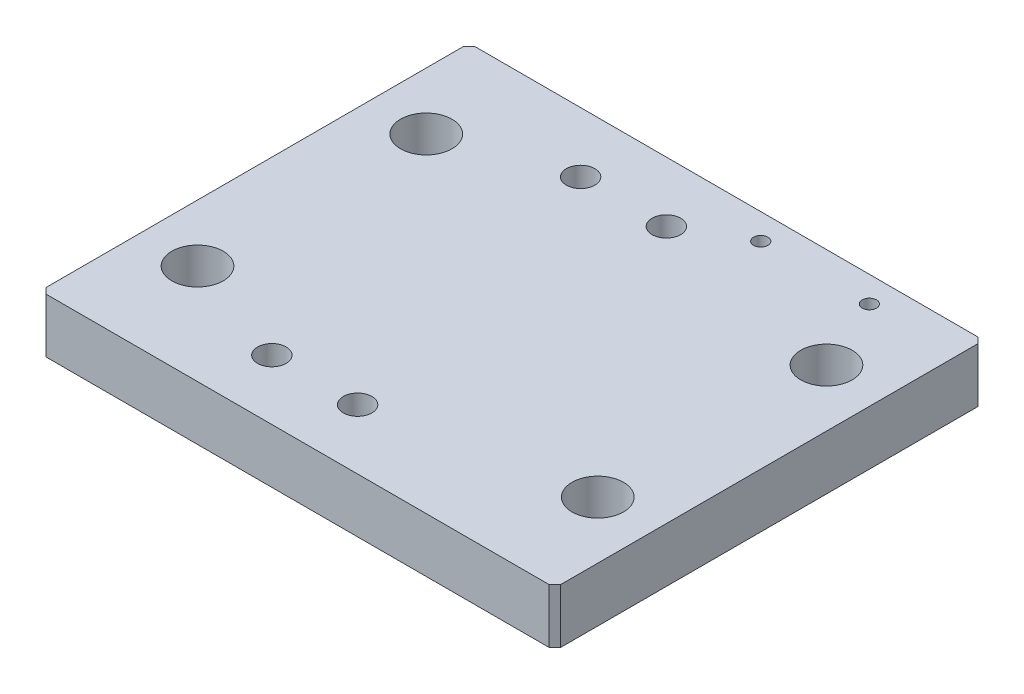
SolidWorks part; units mm, degrees
material "6063-T6"
ref_plane "Front Plane" through (0, 0, 0) normal (0, 0, 1) x (1, 0, 0)
ref_plane "Top Plane" through (0, 0, 0) normal (0, 1, 0) x (1, 0, 0)
ref_plane "Right Plane" through (0, 0, 0) normal (1, 0, 0) x (0, 0, -1)
sketch "Sketch1" plane through (0, 0, 0) normal (0, 1, 0) x (1, 0, 0)
  line L0 (10.5, 33) -> (29.5, 33) construction
  line L1 (-45, 37.5) -> (45, 37.5)
  line L2 (-45, 37.5) -> (-45, -37.5)
  line L3 (-45, -37.5) -> (45, -37.5)
  line L4 (45, 37.5) -> (45, -37.5)
  line L5 (-45, 37.5) -> (45, -37.5) construction
  line L6 (-45, -37.5) -> (45, 37.5) construction
  line L7 (35, 20) -> (-35, 20) construction
  line L8 (35, 20) -> (35, -20) construction
  line L9 (35, -20) -> (-35, -20) construction
  line L10 (-35, 20) -> (-35, -20) construction
  line L11 (35, 20) -> (-35, -20) construction
  line L12 (35, -20) -> (-35, 20) construction
  line L13 (-15, 27) -> (0, 27) construction
  line L14 (-15, 27) -> (-15, -27) construction
  line L15 (-15, -27) -> (0, -27) construction
  line L16 (0, 27) -> (0, -27) construction
  point P0 (0, 0)
  point P6 (0, 0)
  point P17 (20, 33)
  dimension "B" = 15
  dimension "A" = 54
  dimension "D3" = 70
  dimension "D4" = 40
  dimension "D6" = 10
  dimension "D7" = 19
  dimension "D8" = 20
  dimension "D9" = 33
  dimension "C" = 75
extrude "Boss-Extrude1" add sketch "Sketch1" along normal blind 9.525
hole_wizard "M8 Clearance Hole1" positions "Sketch2" profile "Sketch3" hole size "M8" standard "ANSI Metric" end condition through all
sketch "Sketch2" plane through (0, 9.525, 0) normal (0, 1, 0) x (1, 0, 0)
  point P0 (-35, 20)
  point P3 (35, 20)
  point P6 (35, -20)
  point P9 (-35, -20)
sketch "Sketch3" plane through (-35, 9.525, -20) normal (1, 0, 0) x (0, 0, 1)
  line L0 (0, 0) -> (0, 9.525)
  line L1 (0, 9.525) -> (4.5, 9.525)
  line L2 (4.5, 9.525) -> (4.5, 0)
  line L5 (4.5, 0) -> (0, 0)
  line L11 (0, -6.35) -> (0, 107.95) construction
  dimension "Thru Hole Dia." = 9
  dimension "Thru Hole Depth" = 9.525
hole_wizard "Fixed M6x1.0 Tapped Hole1" positions "Sketch4" profile "Sketch5" tap size "M6x1.0" standard "ANSI Metric" end condition up to next
sketch "Sketch4" plane through (0, 9.525, 0) normal (0, 1, 0) x (1, 0, 0)
  point P0 (-15, 27)
  point P3 (0, 27)
  point P6 (0, -27)
  point P9 (-15, -27)
sketch "Sketch5" plane through (-15, 9.525, -27) normal (1, 0, 0) x (0, 0, 1)
  line L0 (0, 0) -> (0, 9.525)
  line L1 (0, 9.525) -> (2.5, 9.525)
  line L2 (2.5, 9.525) -> (2.5, 0)
  line L5 (2.5, 0) -> (0, 0)
  line L11 (0, -6.35) -> (0, 107.95) construction
  dimension "Thru Tap Drill Dia." = 5
  dimension "Thru Tap Drill Depth" = 9.525
cosmetic thread "Hole Thread1"
cosmetic thread "Hole Thread2"
cosmetic thread "Hole Thread3"
cosmetic thread "Hole Thread4"
hole_wizard "Free M6x1.0 Tapped Hole2" [suppressed] positions "Sketch8" profile "Sketch9" tap size "M6x1.0" standard "ANSI Metric"
sketch "Sketch8" plane through (0, 9.525, 0) normal (0, 1, 0) x (1, 0, 0)
  line L0 (-13, 23) -> (0, 23) construction
  line L1 (-13, -23) -> (0, -23) construction
  line L3 (0, -23) -> (0, 23) construction
  line L4 (0, 23) -> (0, -23) construction
  line L5 (-13, 23) -> (-13, -23) construction
  point P0 (0, 23)
  point P3 (0, -23)
sketch "Sketch9" plane through (0, 9.525, -23) normal (1, 0, 0) x (0, 0, 1)
  line L0 (0, 0) -> (0, 9.525)
  line L1 (0, 9.525) -> (2.5, 9.525)
  line L2 (2.5, 9.525) -> (2.5, 0)
  line L5 (2.5, 0) -> (0, 0)
  line L11 (0, -6.35) -> (0, 107.95) construction
  dimension "Thru Tap Drill Dia." = 5
  dimension "Thru Tap Drill Depth" = 9.525
cosmetic thread "Hole Thread7" [suppressed] parameters "D2"=6
cosmetic thread "Hole Thread8" [suppressed] parameters "D2"=6
hole_wizard "M3x0.5 Tapped Hole1" positions "Sketch6" profile "Sketch7" tap size "M3x0.5" standard "ANSI Metric" end condition up to next
sketch "Sketch6" plane through (0, 9.525, 0) normal (0, 1, 0) x (1, 0, 0)
  point P0 (10.5, 33)
  point P3 (29.5, 33)
sketch "Sketch7" plane through (10.5, 9.525, -33) normal (1, 0, 0) x (0, 0, 1)
  line L0 (0, 0) -> (0, 9.525)
  line L1 (0, 9.525) -> (1.25, 9.525)
  line L2 (1.25, 9.525) -> (1.25, 0)
  line L5 (1.25, 0) -> (0, 0)
  line L11 (0, -6.35) -> (0, 107.95) construction
  dimension "Thru Tap Drill Dia." = 2.5
  dimension "Thru Tap Drill Depth" = 9.525
cosmetic thread "Hole Thread5"
cosmetic thread "Hole Thread6"
chamfer "Chamfer1" distance 1 angle 45 4 edges at (45, 4.7625, 37.5) (-45, 4.7625, 37.5) (45, 4.7625, -37.5) (-45, 4.7625, -37.5)
